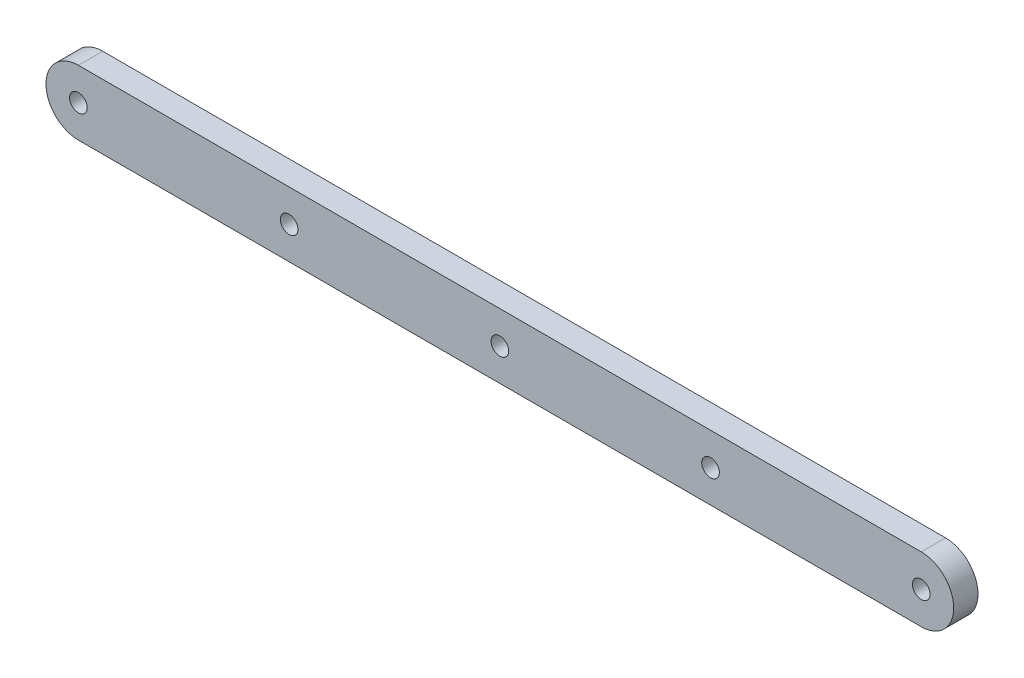
SolidWorks part; units mm, degrees
ref_plane "Front Plane" through (0, 0, 0) normal (0, 0, 1) x (1, 0, 0)
ref_plane "Top Plane" through (0, 0, 0) normal (0, 1, 0) x (1, 0, 0)
ref_plane "Right Plane" through (0, 0, 0) normal (1, 0, 0) x (0, 0, -1)
sketch "Sketch1" plane through (0, 0, 0) normal (0, 0, 1) x (1, 0, 0)
  line L0 (-82.55, 0) -> (82.55, 0)
  line L1 (-82.55, 12.7) -> (82.55, 12.7)
  line L2 (0, 12.7) -> (0, 0) construction
  arc A0 (82.55, 0) -> (82.55, 12.7) centre (82.55, 6.35) ccw
  arc A1 (-82.55, 0) -> (-82.55, 12.7) centre (-82.55, 6.35) cw
  dimension "D1" = 12.7
  dimension "D2" = 82.55
extrude "Boss-Extrude1" add sketch "Sketch1" along normal blind 4.7625
sketch "Sketch2" plane through (0, 0, 4.7625) normal (0, 0, 1) x (1, 0, 0)
  line L0 (82.55, 12.7) -> (82.55, 0) construction
  line L1 (-82.55, 12.7) -> (-82.55, 0) construction
  line L2 (82.55, 6.35) -> (-82.55, 6.35) construction
hole_wizard "#8-32 Tapped Hole1" positions "Sketch4" profile "Sketch3" tap size "#8-32" standard "ANSI Inch"
sketch "Sketch4" plane through (0, 0, 4.7625) normal (0, 0, 1) x (1, 0, 0)
  line L0 (82.55, 6.35) -> (-82.55, 6.35) construction
  point P0 (-82.55, 6.35)
  point P3 (82.55, 6.35)
  point P7 (0, 6.35)
  point P12 (41.2715, 6.35)
  point P14 (-41.2761, 6.35)
sketch "Sketch3" plane through (-82.55, 6.35, 4.7625) normal (1, 0, 0) x (0, -1, 0)
  line L0 (0, 0) -> (0, 13.2298)
  line L1 (0, 13.2298) -> (1.7272, 12.192)
  line L2 (1.7272, 12.192) -> (1.7272, 0)
  line L5 (1.7272, 0) -> (0, 0)
  line L10 (0, 13.2298) -> (-1.7272, 12.192) construction
  line L11 (0, -6.35) -> (0, 107.95) construction
  dimension "Tap Drill Dia." = 3.4544
  dimension "Tap Drill Depth" = 12.192
  dimension "Drill Angle" = 118
cosmetic thread "Hole Thread1"
cosmetic thread "Hole Thread2"
cosmetic thread "Hole Thread3"
cosmetic thread "Hole Thread4"
cosmetic thread "Hole Thread5"
